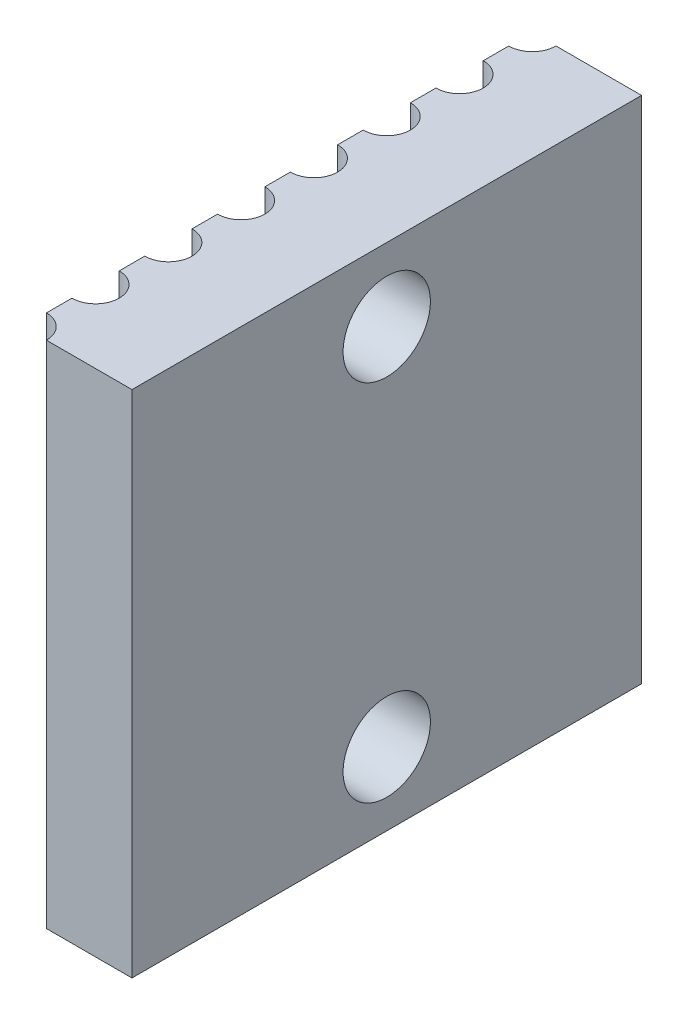
SolidWorks part; units mm, degrees
ref_plane "Front Plane" through (0, 0, 0) normal (0, 0, 1) x (1, 0, 0)
ref_plane "Top Plane" through (0, 0, 0) normal (0, 1, 0) x (1, 0, 0)
ref_plane "Right Plane" through (0, 0, 0) normal (1, 0, 0) x (0, 0, -1)
sketch "Sketch1" plane through (0, 0, 0) normal (0, 1, 0) x (1, 0, 0)
  line L0 (0, 0) -> (3, 0)
  line L3 (3, 0) -> (3, -14)
  line L4 (3, -14) -> (0, -14)
  line L5 (0, -14) -> (0, 0)
  dimension "D3" = 14
  dimension "D4" = 3
extrude "Boss-Extrude1" add sketch "Sketch1" along normal blind 14
sketch "Sketch2" plane through (0, 0, 0) normal (0, 1, 0) x (1, 0, 0)
  circle A0 centre (0, 0) radius 0.65
  circle A1 centre (0, -2) radius 0.65
  circle A2 centre (0, -4) radius 0.65
  circle A3 centre (0, -6) radius 0.65
  circle A4 centre (0, -8) radius 0.65
  circle A5 centre (0, -10) radius 0.65
  circle A6 centre (0, -12) radius 0.65
  circle A7 centre (0, -14) radius 0.65
  dimension "D1" = 1.3
  dimension "D2" = 8
extrude "Cut-Extrude1" cut sketch "Sketch2" along normal through all
hole_wizard "M2 Clearance Hole1" positions "Sketch5" profile "Sketch6" hole size "M2" standard "ISO" end condition up to next
sketch "Sketch5" plane through (3, 0, 0) normal (1, 0, 0) x (0, 0, -1)
  line L0 (-7, 14) -> (-7, 0) construction
  line L1 (-14, 14) -> (0, 14) construction
  line L2 (-14, 0) -> (0, 0) construction
  line L4 (-14, 7) -> (0, 7) construction
  line L5 (-14, 14) -> (-14, 0) construction
  line L8 (0, 14) -> (0, 0) construction
  point P0 (-7, 12)
  point P19 (-7, 2)
  dimension "D1" = 2
sketch "Sketch6" plane through (3, 12, 7) normal (0, 1, 0) x (0, 0, -1)
  line L0 (0, 0) -> (0, 3)
  line L1 (0, 3) -> (1.2, 3)
  line L2 (1.2, 3) -> (1.2, 0)
  line L5 (1.2, 0) -> (0, 0)
  line L11 (0, -6.35) -> (0, 107.95) construction
  dimension "Thru Hole Dia." = 2.4
  dimension "Thru Hole Depth" = 3
